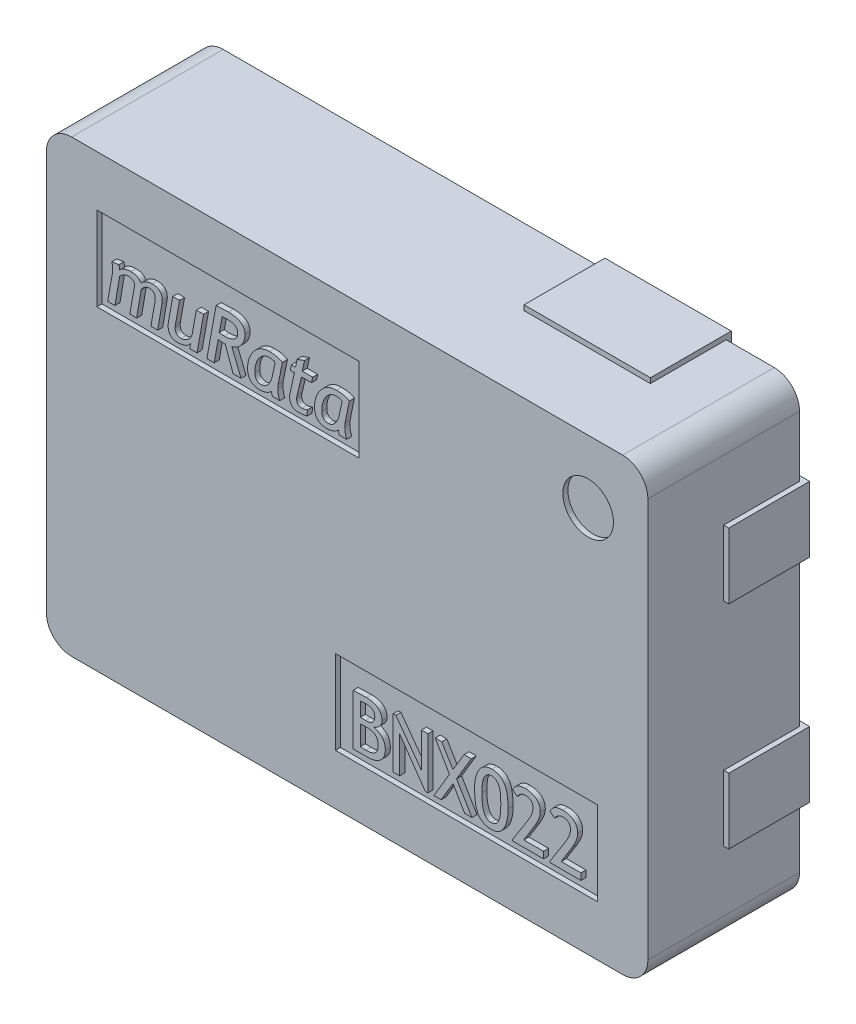
SolidWorks part; units mm, degrees
ref_plane "Спереди" through (0, 0, 0) normal (0, 0, 1) x (1, 0, 0)
ref_plane "Сверху" through (0, 0, 0) normal (0, 1, 0) x (1, 0, 0)
ref_plane "Справа" through (0, 0, 0) normal (1, 0, 0) x (0, 0, -1)
sketch "Эскиз1" plane through (0, 0, 0) normal (0, 0, 1) x (1, 0, 0)
  line L0 (0, 15.2044) -> (0, -17.4908) construction
  line L1 (-21.7658, 0) -> (30.1148, 0) construction
  line L2 (-6.05, -2.75) -> (-5.05, -2.75)
  line L3 (-6.05, 4.55) -> (6.05, 4.55) construction
  line L4 (-6.05, 4.55) -> (-6.05, -4.55) construction
  line L5 (-6.05, -4.55) -> (6.05, -4.55) construction
  line L6 (6.05, 4.55) -> (6.05, -4.55) construction
  line L7 (-6.05, 2.75) -> (-5.05, 2.75)
  line L8 (-6.05, 2.75) -> (-6.05, 1.45)
  line L9 (-6.05, 1.45) -> (-5.05, 1.45)
  line L10 (-5.05, 2.75) -> (-5.05, 1.45)
  line L11 (-5.05, -2.75) -> (-5.05, -1.45)
  line L12 (-6.05, -1.45) -> (-5.05, -1.45)
  line L13 (-6.05, -2.75) -> (-6.05, -1.45)
  line L14 (6.05, -2.75) -> (6.05, -1.45)
  line L15 (6.05, -1.45) -> (5.05, -1.45)
  line L16 (5.05, -2.75) -> (5.05, -1.45)
  line L17 (5.05, 2.75) -> (5.05, 1.45)
  line L18 (6.05, 1.45) -> (5.05, 1.45)
  line L19 (6.05, 2.75) -> (6.05, 1.45)
  line L20 (6.05, 2.75) -> (5.05, 2.75)
  line L21 (6.05, -2.75) -> (5.05, -2.75)
  line L23 (-2.5, -4.55) -> (4.5, -4.55)
  line L24 (-2.5, -4.55) -> (-2.5, -4.25)
  line L25 (-2.5, -4.25) -> (4.5, -4.25)
  line L26 (4.5, -4.55) -> (4.5, -4.25)
  line L27 (2, 4.55) -> (4.5, 4.55)
  line L28 (2, 4.55) -> (2, 4.25)
  line L29 (2, 4.25) -> (4.5, 4.25)
  line L30 (4.5, 4.55) -> (4.5, 4.25)
  dimension "D1" = 9.1
  dimension "D2" = 12.1
  dimension "D3" = 1.3
  dimension "D4" = 1
  dimension "D5" = 1.8
  dimension "D6" = 7
  dimension "D7" = 0.3
  dimension "D8" = 1.55
  dimension "D9" = 0.3
  dimension "D10" = 2.5
  dimension "D11" = 1.55
extrude "Бобышка-Вытянуть1" add sketch "Эскиз1" along normal blind 1.6
ref_plane "Плоскость1" through (0, 0, 0.1) normal (0, 0, 1) x (1, 0, 0)
sketch "Эскиз2" plane through (0, 0, 0.1) normal (0, 0, 1) x (1, 0, 0)
  line L0 (-6.05, -1.45) -> (-6.05, -2.75) construction
  line L1 (-5.95, 4.45) -> (5.95, 4.45)
  line L2 (-5.95, 4.45) -> (-5.95, -4.45)
  line L3 (-5.95, -4.45) -> (5.95, -4.45)
  line L4 (5.95, 4.45) -> (5.95, -4.45)
  line L6 (-2.5, -4.55) -> (4.5, -4.55) construction
  dimension "D1" = 11.9
  dimension "D2" = 8.9
  dimension "D3" = 0.1
  dimension "D4" = 0.1
extrude "Бобышка-Вытянуть2" add sketch "Эскиз2" along normal blind 3
sketch "Эскиз3" plane through (0, 0, 3.1) normal (0, 0, 1) x (1, 0, 0)
  line L1 (-4.95, 3.45) -> (0.232, 3.45)
  line L2 (-4.95, 3.45) -> (-4.95, 1.7907)
  line L3 (-4.95, 1.7907) -> (0.232, 1.7907)
  line L4 (0.232, 3.45) -> (0.232, 1.7907)
  line L5 (5.95, -4.45) -> (5.95, 4.45) construction
  line L6 (-0.232, -1.7907) -> (4.95, -1.7907)
  line L7 (-0.232, -1.7907) -> (-0.232, -3.45)
  line L8 (-0.232, -3.45) -> (4.95, -3.45)
  line L9 (4.95, -1.7907) -> (4.95, -3.45)
  line L10 (-5.95, -4.45) -> (5.95, -4.45) construction
  line L11 (5.95, 4.45) -> (-5.95, 4.45) construction
  line L12 (-5.95, 4.45) -> (-5.95, -4.45) construction
  circle A0 centre (4.7682, 3.204) radius 0.5
  dimension "D1" = 1
  dimension "D2" = 1
  dimension "D3" = 1
  dimension "D4" = 1
  dimension "D5" = 1
extrude "Вырез-Вытянуть1" cut sketch "Эскиз3" against normal blind 0.1
sketch "Эскиз4" plane through (0, 0, 3) normal (0, 0, 1) x (1, 0, 0)
  line L0 (-4.95, 1.9907) -> (0.232, 1.9907) construction
  line L1 (-4.95, 3.45) -> (-4.95, 1.7907) construction
  line L2 (0.232, 1.7907) -> (0.232, 3.45) construction
  line L3 (-0.232, -3.25) -> (4.95, -3.25) construction
  line L4 (-0.232, -1.7907) -> (-0.232, -3.45) construction
  line L5 (4.95, -3.45) -> (4.95, -1.7907) construction
  line L6 (-4.95, 1.7907) -> (0.232, 1.7907) construction
  line L7 (-0.232, -3.45) -> (4.95, -3.45) construction
  text T0 "muRata" font "Trebuchet MS" height 1
  text T1 "BNX022" font "Trebuchet MS" height 1
  dimension "D1" = 0.2
  dimension "D2" = 0.2
extrude "Бобышка-Вытянуть3" add sketch "Эскиз4" along normal blind 0.1
fillet "Скругление1" radius 0.5 4 edges at (-5.95, -4.45, 1.6) (5.95, -4.45, 1.6) (5.95, 4.45, 1.6) (-5.95, 4.45, 1.6)
